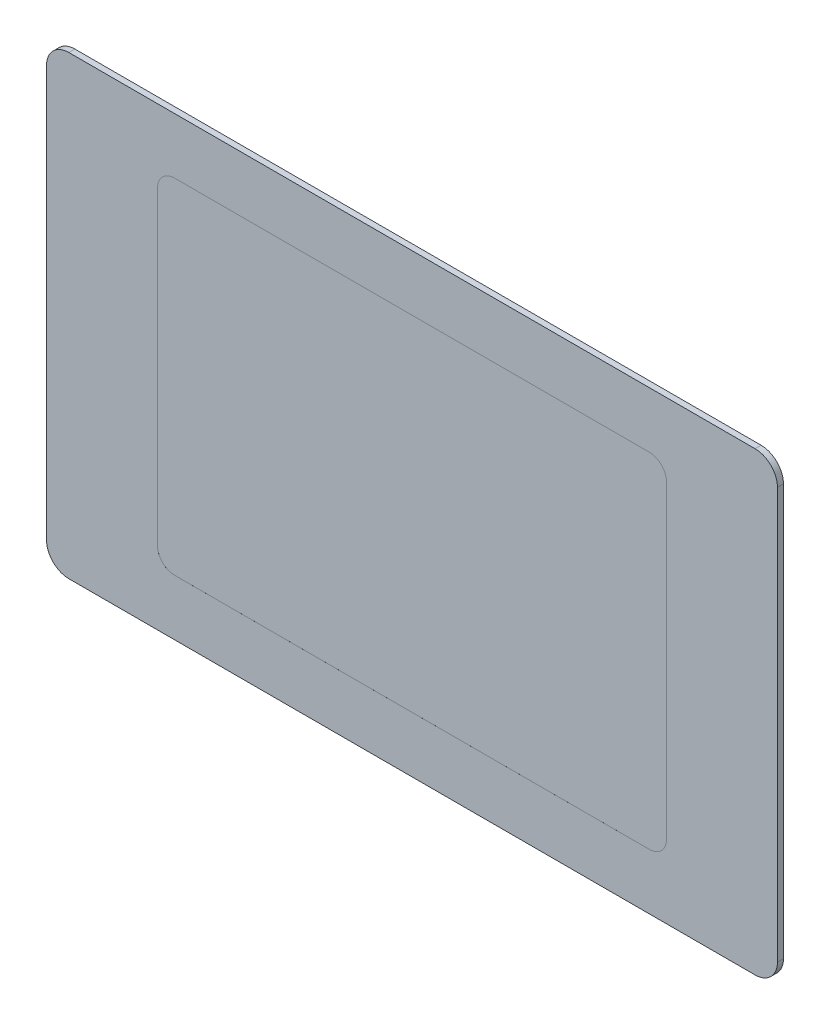
SolidWorks part; units mm, degrees
ref_plane "Спереди" through (0, 0, 0) normal (0, 0, 1) x (1, 0, 0)
ref_plane "Сверху" through (0, 0, 0) normal (0, 1, 0) x (1, 0, 0)
ref_plane "Справа" through (0, 0, 0) normal (1, 0, 0) x (0, 0, -1)
sketch "Эскиз1" plane through (0, 0, 0) normal (0, 0, 1) x (1, 0, 0)
  line L1 (-39.9, 26.5) -> (39.9, 26.5)
  line L2 (-42.5, 23.9) -> (-42.5, -23.9)
  line L3 (-39.9, -26.5) -> (39.9, -26.5)
  line L4 (42.5, 23.9) -> (42.5, -23.9)
  line L5 (-42.5, 26.5) -> (42.5, -26.5) construction
  line L6 (-42.5, -26.5) -> (42.5, 26.5) construction
  arc A0 (-39.9, 26.5) -> (-42.5, 23.9) centre (-39.9, 23.9) ccw
  arc A1 (-42.5, -23.9) -> (-39.9, -26.5) centre (-39.9, -23.9) ccw
  arc A2 (39.9, -26.5) -> (42.5, -23.9) centre (39.9, -23.9) ccw
  arc A3 (39.9, 26.5) -> (42.5, 23.9) centre (39.9, 23.9) cw
  point P0 (0, 0)
  dimension "D3" = 2.6
  dimension "D1" = 85
  dimension "D2" = 53
extrude "Бобышка-Вытянуть1" add sketch "Эскиз1" along normal blind 0.7
sketch "Эскиз2" plane through (0, 0, 0.7) normal (0, 0, 1) x (1, 0, 0)
  line L0 (-42.5, -23.9) -> (-42.5, 23.9)
  line L1 (-39.9, 26.5) -> (39.9, 26.5)
  line L2 (42.5, 23.9) -> (42.5, -23.9)
  line L3 (39.9, -26.5) -> (-39.9, -26.5)
  line L7 (-27.6, 20) -> (27.6, 20)
  line L12 (-29.6, 18) -> (-29.6, -18)
  line L13 (-27.6, -20) -> (27.6, -20)
  line L14 (29.6, 18) -> (29.6, -18)
  line L15 (-29.6, 20) -> (29.6, -20) construction
  line L16 (-29.6, -20) -> (29.6, 20) construction
  arc A0 (-42.5, 23.9) -> (-39.9, 26.5) centre (-39.9, 23.9) cw
  arc A1 (42.5, 23.9) -> (39.9, 26.5) centre (39.9, 23.9) ccw
  arc A2 (42.5, -23.9) -> (39.9, -26.5) centre (39.9, -23.9) cw
  arc A3 (-39.9, -26.5) -> (-42.5, -23.9) centre (-39.9, -23.9) cw
  arc A10 (-29.6, -18) -> (-27.6, -20) centre (-27.6, -18) ccw
  arc A11 (27.6, -20) -> (29.6, -18) centre (27.6, -18) ccw
  arc A12 (27.6, 20) -> (29.6, 18) centre (27.6, 18) cw
  arc A13 (-27.6, 20) -> (-29.6, 18) centre (-27.6, 18) ccw
  point P0 (0, 0)
  dimension "D3" = 2
  dimension "D1" = 59.2
  dimension "D2" = 40
extrude "Бобышка-Вытянуть2" add sketch "Эскиз2" along normal blind 0.001
